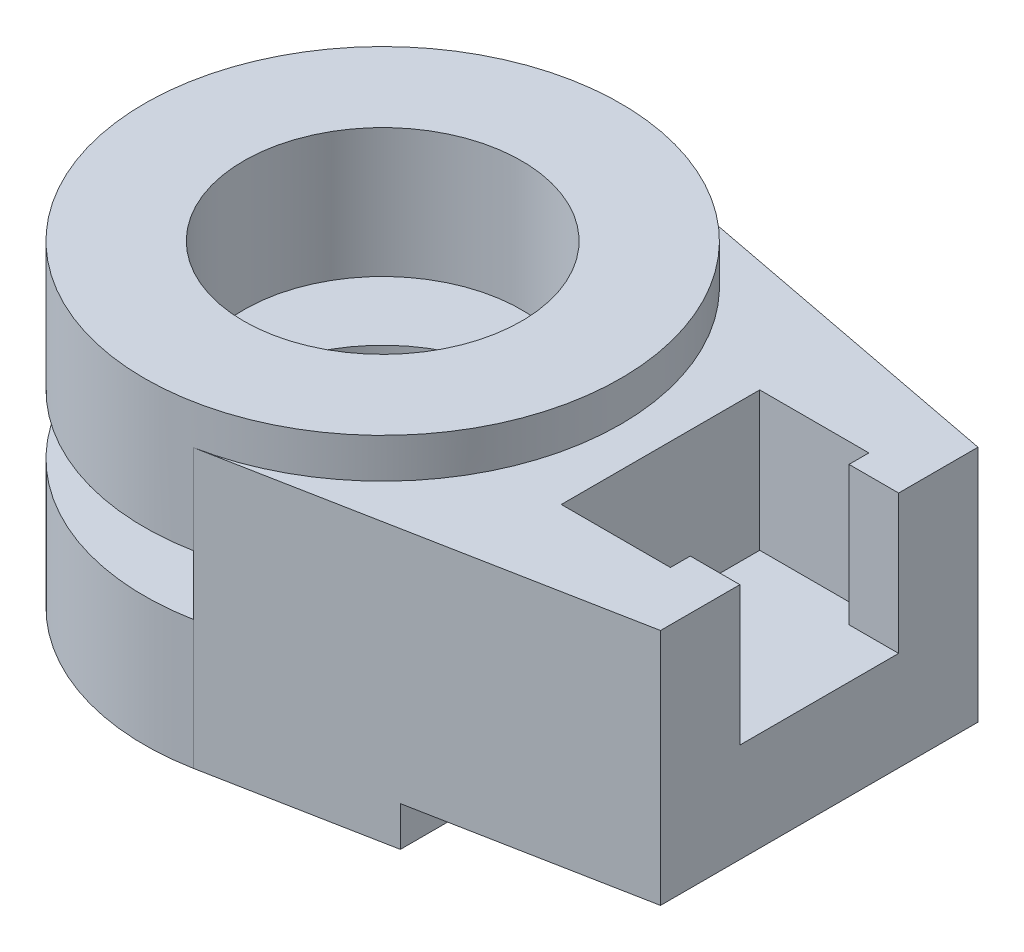
SolidWorks part; units mm, degrees
ref_plane "前基準面" through (0, 0, 0) normal (0, 0, 1) x (1, 0, 0)
ref_plane "上基準面" through (0, 0, 0) normal (0, 1, 0) x (1, 0, 0)
ref_plane "右基準面" through (0, 0, 0) normal (1, 0, 0) x (0, 0, -1)
sketch "草圖1" plane through (0, 0, 0) normal (0, 1, 0) x (1, 0, 0)
  circle A0 centre (0, 0) radius 48
  dimension "D1" = 96
extrude "填料-伸長1" add sketch "草圖1" along normal blind 64
sketch "草圖2" plane through (0, 0, 0) normal (0, 0, 1) x (1, 0, 0)
  line L0 (-48, 64) -> (-48, 0) construction
  line L1 (-48, 38) -> (12, 38)
  line L2 (-48, 38) -> (-48, 26)
  line L3 (-48, 26) -> (12, 26)
  line L5 (12, 32) -> (-64.4172, 32) construction
  line L6 (-48, 0) -> (48, 0) construction
  arc A0 (12, 26) -> (12, 38) centre (12, 32) ccw
  dimension "D1" = 60
  dimension "D2" = 32
  dimension "D3" = 12
extrude "除料-伸長1" cut sketch "草圖2" against normal mid plane 134
ref_plane "平面1" through (0, 56, 0) normal (0, 1, 0) x (1, 0, 0)
sketch "草圖3" plane through (0, 56, 0) normal (0, 1, 0) x (1, 0, 0)
  line L0 (0, 0) -> (166.6315, 0) construction
  line L1 (88, -32) -> (88, 32)
  line L2 (88, 32) -> (9.0396, 47.1411)
  line L3 (88, -32) -> (9.0396, -47.1411)
  circle A0 centre (0, 0) radius 48 construction
  arc A1 (9.0396, -47.1411) -> (9.0396, 47.1411) centre (0, 0) ccw
  point P10 (88, 0)
  dimension "D1" = 88
  dimension "D2" = 64
extrude "填料-伸長2" add sketch "草圖3" against normal blind 56
sketch "草圖4" plane through (0, 56, 0) normal (0, 1, 0) x (1, 0, 0)
  line L0 (0, 0) -> (109.9994, 0) construction
  line L1 (88, -16) -> (88, 16)
  line L2 (88, -32) -> (88, 32) construction
  line L3 (88, 16) -> (78, 16)
  line L4 (78, 16) -> (78, 20)
  line L5 (78, 20) -> (56, 20)
  line L6 (56, 20) -> (56, -20)
  line L7 (78, -20) -> (56, -20)
  line L8 (78, -16) -> (78, -20)
  line L9 (88, -16) -> (78, -16)
  point P12 (56, 0)
  point P13 (88, 0)
  dimension "D1" = 22
  dimension "D2" = 10
  dimension "D3" = 32
  dimension "D4" = 40
extrude "除料-伸長2" cut sketch "草圖4" against normal blind 28
sketch "草圖5" plane through (0, 0, 0) normal (0, 0, 1) x (1, 0, 0)
  line L1 (88, 0) -> (44, 0)
  line L2 (88, 0) -> (88, 8)
  line L3 (88, 8) -> (44, 8)
  line L4 (44, 0) -> (44, 8)
  dimension "D1" = 8
  dimension "D2" = 44
extrude "除料-伸長3" cut sketch "草圖5" against normal mid plane 108
sketch "草圖6" plane through (0, 64, 0) normal (0, 1, 0) x (1, 0, 0)
  circle A0 centre (0, 0) radius 28
  dimension "D1" = 56
extrude "除料-伸長4" cut sketch "草圖6" against normal through all
